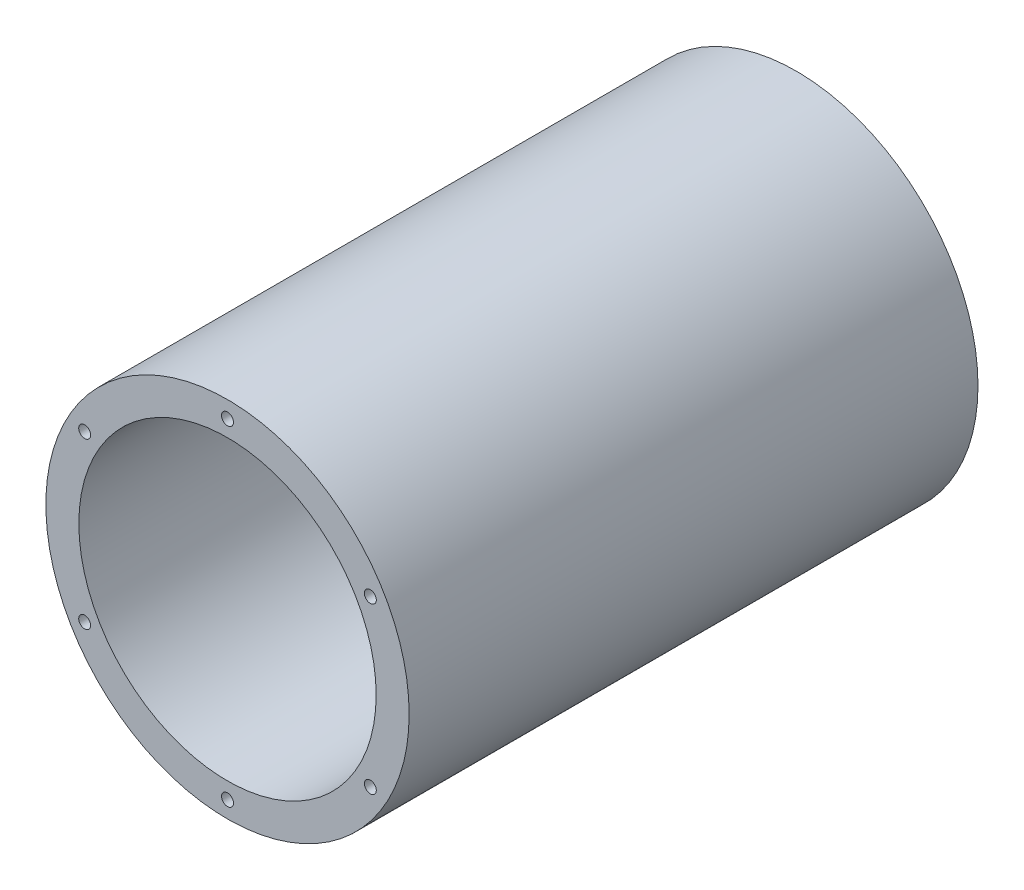
SolidWorks part; units mm, degrees
material "AISI 1020 钢，冷轧"
ref_plane "前视基准面" through (0, 0, 0) normal (0, 0, 1) x (1, 0, 0)
ref_plane "上视基准面" through (0, 0, 0) normal (0, 1, 0) x (1, 0, 0)
ref_plane "右视基准面" through (0, 0, 0) normal (1, 0, 0) x (0, 0, -1)
sketch "草图1" plane through (0, 0, 0) normal (0, 0, 1) x (1, 0, 0)
  circle A0 centre (0, 0) radius 38
  circle A1 centre (0, 0) radius 31.1
  dimension "D1" = 76
  dimension "D2" = 62.2
extrude "凸台-拉伸1" add sketch "草图1" along normal mid plane 119
hole_wizard "M3 螺纹孔1" positions "草图3" profile "草图2" tap size "M3" standard "GB"
sketch "草图3" plane through (0, 0, 59.5) normal (0, 0, 1) x (1, 0, 0)
  point P0 (0, 34.5)
  point P10 (29.8779, 17.25)
  point P11 (29.8779, -17.25)
  point P12 (0, -34.5)
  point P13 (-29.8779, -17.25)
  point P14 (-29.8779, 17.25)
  dimension "D1" = 34.5
  dimension "D2" = 6
sketch "草图2" plane through (0, 34.5, 59.5) normal (1, 0, 0) x (0, -1, 0)
  line L0 (0, 0) -> (0, 9.2511)
  line L1 (0, 9.2511) -> (1.25, 8.5)
  line L2 (1.25, 8.5) -> (1.25, 0)
  line L5 (1.25, 0) -> (0, 0)
  line L10 (0, 9.2511) -> (-1.25, 8.5) construction
  line L11 (0, -6.35) -> (0, 107.95) construction
  dimension "螺纹孔钻头直径" = 2.5
  dimension "螺纹孔钻头深度" = 8.5
  dimension "导头角度" = 118
cosmetic thread "孔螺蚊线1" parameters "D1"=6, "D2"=3
cosmetic thread "孔螺蚊线2" parameters "D1"=6, "D2"=3
cosmetic thread "孔螺蚊线3" parameters "D1"=6, "D2"=3
cosmetic thread "孔螺蚊线4" parameters "D1"=6, "D2"=3
cosmetic thread "孔螺蚊线5" parameters "D1"=6, "D2"=3
cosmetic thread "孔螺蚊线6" parameters "D1"=6, "D2"=3
mirror "镜向1" about plane through (0, 0, 0) normal (0, 0, 1) of "M3 螺纹孔1"
